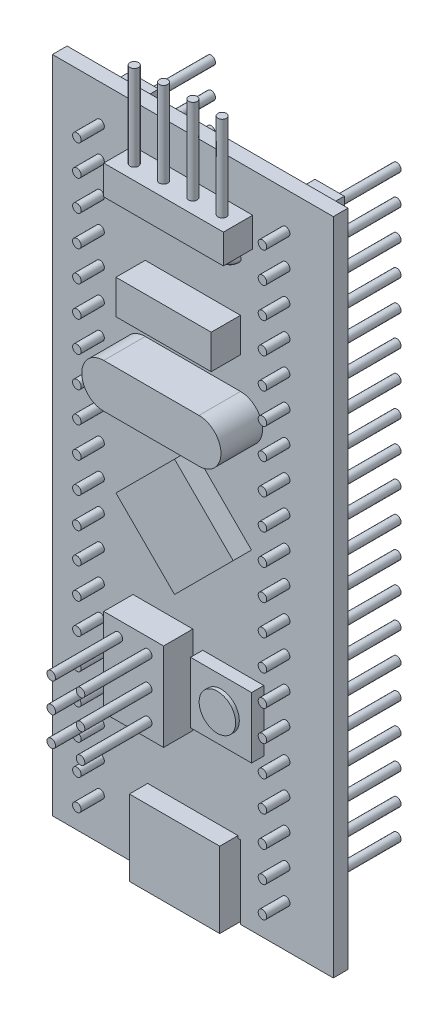
SolidWorks part; units mm, degrees
material "Плата обработки данных, простая"
ref_plane "Спереди" through (0, 0, 0) normal (0, 0, 1) x (1, 0, 0)
ref_plane "Сверху" through (0, 0, 0) normal (0, 1, 0) x (1, 0, 0)
ref_plane "Справа" through (0, 0, 0) normal (1, 0, 0) x (0, 0, -1)
sketch "Эскиз1" plane through (0, 0, 0) normal (0, 0, 1) x (1, 0, 0)
  line L0 (0.4001, -30.8708) -> (0.4001, 23.1292) construction
  line L1 (-11.0999, 23.1292) -> (11.9001, 23.1292)
  line L2 (-11.0999, 23.1292) -> (-11.0999, -30.8708)
  line L3 (-11.0999, -30.8708) -> (11.9001, -30.8708)
  line L4 (11.9001, 23.1292) -> (11.9001, -30.8708)
  line L5 (-11.0999, -3.8708) -> (11.9001, -3.8708) construction
  dimension "D1" = 23
  dimension "D2" = 54
extrude "PCB" add sketch "Эскиз1" along normal blind 1.2
sketch "Эскиз2" plane through (0, 0, 0) normal (0, 0, -1) x (-1, 0, 0)
  line L0 (-0.4001, 23.1292) -> (-0.4001, -30.8708) construction
  line L1 (-11.9001, 23.1292) -> (11.0999, 23.1292) construction
  line L2 (11.0999, -30.8708) -> (-11.9001, -30.8708) construction
  line L3 (-9.2001, 21.4292) -> (-9.2001, -29.1708)
  line L4 (5.9999, 21.4292) -> (8.3999, 21.4292)
  line L5 (5.9999, 21.4292) -> (5.9999, -29.1708)
  line L6 (5.9999, -29.1708) -> (8.3999, -29.1708)
  line L7 (8.3999, 21.4292) -> (8.3999, -29.1708)
  line L8 (-6.8001, -29.1708) -> (-9.2001, -29.1708)
  line L9 (-6.8001, 21.4292) -> (-6.8001, -29.1708)
  line L10 (-6.8001, 21.4292) -> (-9.2001, 21.4292)
  line L11 (-0.4001, -3.8708) -> (-7.8164, -3.8708) construction
  point P16 (-6.8001, -3.8708)
  dimension "D1" = 2.4
  dimension "D2" = 50.6
  dimension "D3" = 17.6
extrude "GPIO Pin Blocks" add sketch "Эскиз2" along normal blind 2.4
sketch "Эскиз3" plane through (0, 0, -2.4) normal (0, 0, -1) x (-1, 0, 0)
  circle A0 centre (-8.0001, 20.1329) radius 0.35
  circle A1 centre (7.1999, 20.1329) radius 0.35
  circle A2 centre (7.1999, 17.6329) radius 0.35
  circle A3 centre (7.1999, 15.1329) radius 0.35
  circle A4 centre (7.1999, 12.6329) radius 0.35
  circle A5 centre (7.1999, 10.1329) radius 0.35
  circle A6 centre (7.1999, 7.6329) radius 0.35
  circle A7 centre (7.1999, 5.1329) radius 0.35
  circle A8 centre (7.1999, 2.6329) radius 0.35
  circle A9 centre (7.1999, 0.1329) radius 0.35
  circle A10 centre (7.1999, -2.3671) radius 0.35
  circle A11 centre (7.1999, -4.8671) radius 0.35
  circle A12 centre (7.1999, -7.3671) radius 0.35
  circle A13 centre (7.1999, -9.8671) radius 0.35
  circle A14 centre (7.1999, -12.3671) radius 0.35
  circle A15 centre (7.1999, -14.8671) radius 0.35
  circle A16 centre (7.1999, -17.3671) radius 0.35
  circle A17 centre (7.1999, -19.8671) radius 0.35
  circle A18 centre (7.1999, -22.3671) radius 0.35
  circle A19 centre (7.1999, -24.8671) radius 0.35
  circle A20 centre (7.1999, -27.3671) radius 0.35
  circle A21 centre (-8.0001, 17.6329) radius 0.35
  circle A22 centre (-8.0001, 15.1329) radius 0.35
  circle A23 centre (-8.0001, 12.6329) radius 0.35
  circle A24 centre (-8.0001, 10.1329) radius 0.35
  circle A25 centre (-8.0001, 7.6329) radius 0.35
  circle A26 centre (-8.0001, 5.1329) radius 0.35
  circle A27 centre (-8.0001, 2.6329) radius 0.35
  circle A28 centre (-8.0001, 0.1329) radius 0.35
  circle A29 centre (-8.0001, -2.3671) radius 0.35
  circle A30 centre (-8.0001, -4.8671) radius 0.35
  circle A31 centre (-8.0001, -7.3671) radius 0.35
  circle A32 centre (-8.0001, -9.8671) radius 0.35
  circle A33 centre (-8.0001, -12.3671) radius 0.35
  circle A34 centre (-8.0001, -14.8671) radius 0.35
  circle A35 centre (-8.0001, -17.3671) radius 0.35
  circle A36 centre (-8.0001, -19.8671) radius 0.35
  circle A37 centre (-8.0001, -22.3671) radius 0.35
  circle A38 centre (-8.0001, -24.8671) radius 0.35
  circle A39 centre (-8.0001, -27.3671) radius 0.35
  dimension "D1" = 0.7
  dimension "D2" = 2
  dimension "D3" = 20
extrude "GPIO Pins" add sketch "Эскиз3" along normal mid plane 11
sketch "Эскиз4" plane through (0, 0, 1.2) normal (0, 0, 1) x (1, 0, 0)
  line L0 (0.4001, 23.1292) -> (0.4001, -30.8708) construction
  line L1 (-4.4999, 19.9292) -> (5.3001, 19.9292)
  line L2 (-4.4999, 19.9292) -> (-4.4999, 17.5292)
  line L3 (-4.4999, 17.5292) -> (5.3001, 17.5292)
  line L4 (5.3001, 19.9292) -> (5.3001, 17.5292)
  line L5 (-4.4999, -11.8708) -> (0.4001, -11.8708)
  line L6 (-4.4999, -11.8708) -> (-4.4999, -19.0708)
  line L7 (-4.4999, -19.0708) -> (0.4001, -19.0708)
  line L8 (0.4001, -11.8708) -> (0.4001, -19.0708)
  line L9 (-3.4999, 12.3292) -> (4.3001, 12.3292)
  line L10 (-3.4999, 12.3292) -> (-3.4999, 9.5292)
  line L11 (-3.4999, 9.5292) -> (4.3001, 9.5292)
  line L12 (4.3001, 12.3292) -> (4.3001, 9.5292)
  line L13 (11.9001, 23.1292) -> (-11.0999, 23.1292) construction
  line L14 (-11.0999, -30.8708) -> (11.9001, -30.8708) construction
  point P18 (5.3001, 18.7292)
  dimension "D1" = 2.4
  dimension "D2" = 4.9
  dimension "D3" = 4.9
  dimension "D4" = 4.9
  dimension "D5" = 7.8
  dimension "D6" = 3.9
  dimension "D7" = 5.6
  dimension "D8" = 10.4
  dimension "D9" = 2.8
  dimension "D10" = 19
  dimension "D11" = 7.2
extrude "Boot Jumper Block" add sketch "Эскиз4" along normal blind 2.4
sketch "Эскиз7" plane through (0, 0, 3.6) normal (0, 0, 1) x (1, 0, 0)
  line L0 (-4.4999, -11.8708) -> (-4.4999, -19.0708) construction
  line L1 (0.4001, -11.8708) -> (-4.4999, -11.8708) construction
  circle A0 centre (-3.2999, -13.0708) radius 0.35
  circle A1 centre (-0.8999, -13.0708) radius 0.35
  circle A2 centre (-0.8999, -15.4708) radius 0.35
  circle A3 centre (-0.8999, -17.8708) radius 0.35
  circle A4 centre (-3.2999, -15.4708) radius 0.35
  circle A5 centre (-3.2999, -17.8708) radius 0.35
  dimension "D1" = 0.7
  dimension "D2" = 1.2
  dimension "D3" = 1.2
  dimension "D4" = 2
  dimension "D5" = 3
extrude "Boot Jumper Pins" add sketch "Эскиз7" along normal mid plane 11
sketch "Эскиз5" plane through (0, 19.9292, 0) normal (0, 1, 0) x (1, 0, 0)
  line L0 (5.3001, -3.6) -> (-4.4999, -3.6) construction
  circle A0 centre (-3.1999, -2.4) radius 0.35
  circle A1 centre (-0.7999, -2.4) radius 0.35
  circle A2 centre (1.6001, -2.4) radius 0.35
  circle A3 centre (4.0001, -2.4) radius 0.35
  point P4 (0.4001, -3.6)
  dimension "D1" = 0.7
  dimension "D2" = 3.6
  dimension "D3" = 4
extrude "ST Link Pins" add sketch "Эскиз5" along normal blind 7
sketch "Эскиз6" plane through (0, 17.5292, 0) normal (0, -1, 0) x (1, 0, 0)
  line L0 (0.4001, 3.6) -> (0.4001, 1.2) construction
  line L1 (-4.4999, 1.2) -> (5.3001, 1.2) construction
  circle A0 centre (-3.1999, 2.4) radius 0.35
  circle A1 centre (-0.7999, 2.4) radius 0.35
  circle A2 centre (1.6001, 2.4) radius 0.35
  circle A3 centre (4.0001, 2.4) radius 0.35
  dimension "D1" = 0.7
  dimension "D2" = 3.6
  dimension "D3" = 4
revolve "90 Degree ST Link Pins" add sketch "Эскиз6" angle 360 about L1
sketch "Эскиз8" plane through (0, 0, 1.2) normal (0, 0, 1) x (1, 0, 0)
  line L0 (0.4001, 23.1292) -> (0.4001, -30.8708) construction
  line L1 (11.9001, 23.1292) -> (-11.0999, 23.1292) construction
  line L2 (-11.0999, -30.8708) -> (11.9001, -30.8708) construction
  line L3 (-11.0999, -3.8708) -> (11.9001, -3.8708) construction
  line L4 (-11.0999, 23.1292) -> (-11.0999, -30.8708) construction
  line L5 (11.9001, -30.8708) -> (11.9001, 23.1292) construction
  line L6 (-4.3999, -3.8708) -> (0.4001, 0.9292)
  line L7 (0.4001, 0.9292) -> (5.2001, -3.8708)
  line L8 (5.2001, -3.8708) -> (0.4001, -8.6708)
  line L9 (0.4001, -8.6708) -> (-4.3999, -3.8708)
  line L11 (-3.2999, -30.8708) -> (4.1001, -30.8708)
  line L12 (-3.2999, -30.8708) -> (-3.2999, -24.6708)
  line L13 (-3.2999, -24.6708) -> (4.1001, -24.6708)
  line L14 (4.1001, -30.8708) -> (4.1001, -24.6708)
  point P20 (0.4001, -24.6708)
  dimension "D1" = 45
  dimension "D2" = 4.8
  dimension "D3" = 7.4
  dimension "D4" = 6.2
extrude "STM32 Chip" add sketch "Эскиз8" along normal blind 1.5
sketch "Эскиз9" plane through (0, 0, 1.2) normal (0, 0, 1) x (1, 0, 0)
  line L0 (-3.4999, 5.1292) -> (4.3001, 5.1292) construction
  line L1 (-3.4999, 6.9292) -> (4.3001, 6.9292)
  line L2 (-3.4999, 3.3292) -> (4.3001, 3.3292)
  line L3 (4.3001, 12.3292) -> (-3.4999, 12.3292) construction
  arc A0 (-3.4999, 6.9292) -> (-3.4999, 3.3292) centre (-3.4999, 5.1292) ccw
  arc A1 (4.3001, 3.3292) -> (4.3001, 6.9292) centre (4.3001, 5.1292) ccw
  point P2 (0.4001, 5.1292)
  dimension "D1" = 3.6
  dimension "D2" = 9
extrude "Crystal Oscillator" add sketch "Эскиз9" along normal blind 3.4
sketch "Эскиз10" plane through (0, 0, 1.2) normal (0, 0, 1) x (1, 0, 0)
  line L1 (1.2093, -12.9708) -> (6.2093, -12.9708)
  line L2 (1.2093, -12.9708) -> (1.2093, -17.9708)
  line L3 (1.2093, -17.9708) -> (6.2093, -17.9708)
  line L4 (6.2093, -12.9708) -> (6.2093, -17.9708)
  circle A0 centre (3.7093, -15.4708) radius 2.5 construction
  dimension "D1" = 5
extrude "Reset Button Base" add sketch "Эскиз10" along normal blind 1
sketch "Эскиз11" plane through (0, 0, 2.2) normal (0, 0, 1) x (1, 0, 0)
  circle A0 centre (3.7093, -15.4708) radius 1.4951
extrude "Reset Button" add sketch "Эскиз11" along normal blind 0.3
sketch "Эскиз12" plane through (0, -30.8708, 0) normal (0, -1, 0) x (1, 0, 0)
  line L0 (-3.484, 1.2) -> (-3.484, 0)
  line L1 (-4.4999, 1.2) -> (0.4001, 1.2) construction
  line L2 (-11.0999, 0) -> (11.9001, 0) construction
  line L4 (-2.7206, 0.1855) -> (-3.2999, 0.727)
  line L5 (-3.2999, 0.727) -> (-3.2999, 1.2)
  line L6 (-3.2999, 1.2) -> (-3.484, 1.2)
  line L7 (0.4001, 0) -> (0.4001, 2.7) construction
  line L8 (-3.2999, 2.7) -> (4.1001, 2.7) construction
  line L9 (4.1001, 0.727) -> (4.1001, 1.2)
  line L10 (3.5208, 0.1855) -> (4.1001, 0.727)
  line L12 (4.2842, 1.2) -> (4.2842, 0)
  line L13 (4.1001, 1.2) -> (4.2842, 1.2)
  line L14 (-2.7206, 0.1855) -> (3.5208, 0.1855)
  line L15 (4.2842, 0) -> (-3.484, 0)
extrude "Micro USB Port" cut sketch "Эскиз12" against normal blind 6
sketch "Çizim1" plane through (0, -30.8708, 0) normal (0, -1, 0) x (1, 0, 0)
  line L0 (-3.0499, 0.9855) -> (-2.5334, 0.4855)
  line L1 (-2.5334, 0.4855) -> (3.3336, 0.4855)
  line L2 (3.3336, 0.4855) -> (3.8501, 0.9855)
  line L3 (3.8501, 0.9855) -> (-3.0499, 0.9855)
  line L4 (-3.0499, 1.3855) -> (-3.0499, 2.3855)
  line L5 (-3.0499, 2.3855) -> (3.8501, 2.3855)
  line L6 (3.8501, 2.3855) -> (3.8501, 1.3855)
  line L7 (3.8501, 1.3855) -> (-3.0499, 1.3855)
  line L8 (-2.7206, 0.1855) -> (-3.2999, 0.727) construction
  line L9 (4.1001, 0.727) -> (3.5208, 0.1855) construction
  line L10 (3.5208, 0.1855) -> (-2.7206, 0.1855) construction
  line L11 (-3.2999, 2.7) -> (-3.2999, 0.727) construction
  line L12 (4.1001, 1.2) -> (4.1001, 0.727) construction
  dimension "D1" = 1
  dimension "D2" = 1
  dimension "D3" = 0.3
  dimension "D4" = 0.5
  dimension "D5" = 0.25
  dimension "D6" = 0.25
  dimension "D7" = 1
  dimension "D8" = 0.4
extrude "Micro USB Port Cut" cut sketch "Çizim1" against normal blind 5
